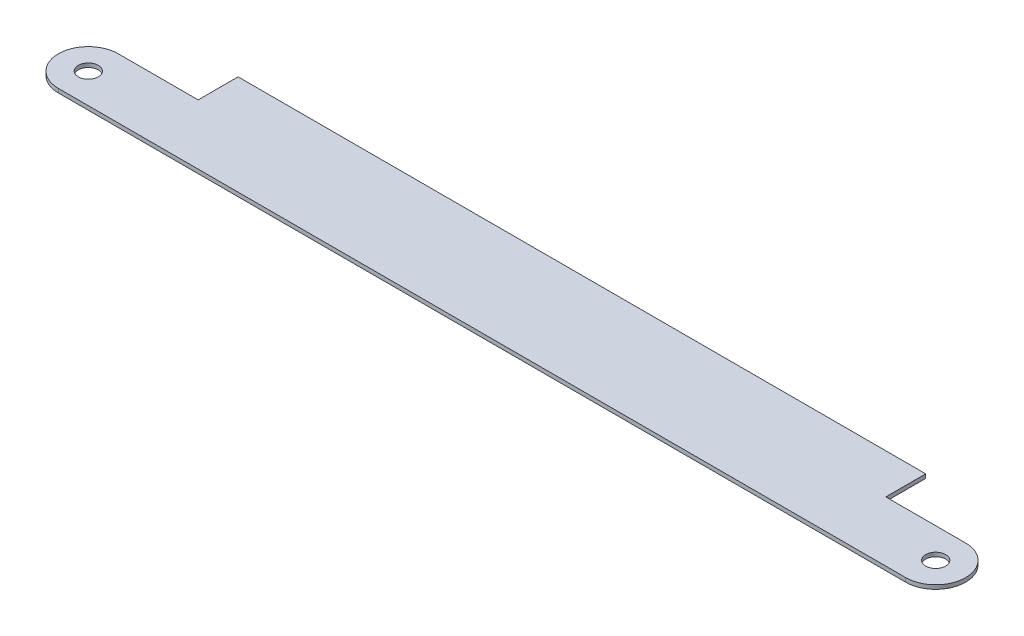
SolidWorks part; units mm, degrees
ref_plane "Front Plane" through (0, 0, 0) normal (0, 0, 1) x (1, 0, 0)
ref_plane "Top Plane" through (0, 0, 0) normal (0, 1, 0) x (1, 0, 0)
ref_plane "Right Plane" through (0, 0, 0) normal (1, 0, 0) x (0, 0, -1)
sketch "Sketch1" plane through (0, 0, 0) normal (0, 1, 0) x (1, 0, 0)
  line L0 (0, 0) -> (212.13, 0) construction
  line L1 (0, 7.5) -> (20, 7.5)
  line L2 (0, -7.5) -> (212.13, -7.5)
  line L3 (0, -7.5) -> (0, 7.5) construction
  line L4 (0, 7.5) -> (212.13, 7.5) construction
  line L5 (212.13, -7.5) -> (212.13, 7.5) construction
  line L6 (0, -7.5) -> (212.13, 7.5) construction
  line L7 (0, 7.5) -> (212.13, -7.5) construction
  line L8 (20, 7.5) -> (20, 17.5)
  line L9 (20, 17.5) -> (192.13, 17.5)
  line L10 (192.13, 17.5) -> (192.13, 7.5)
  line L11 (192.13, 7.5) -> (212.13, 7.5)
  line L12 (106.065, 17.5) -> (106.065, 0) construction
  circle A0 centre (0, 0) radius 2.5
  circle A1 centre (212.13, 0) radius 2.5
  arc A2 (0, 7.5) -> (0, -7.5) centre (0, 0) ccw
  arc A3 (212.13, -7.5) -> (212.13, 7.5) centre (212.13, 0) ccw
  point P5 (106.065, 0)
  dimension "D1" = 5
  dimension "D2" = 15
  dimension "D3" = 20
  dimension "D5" = 10
  dimension "D6" = 212.13
extrude "Boss-Extrude1" add sketch "Sketch1" along normal blind 1
